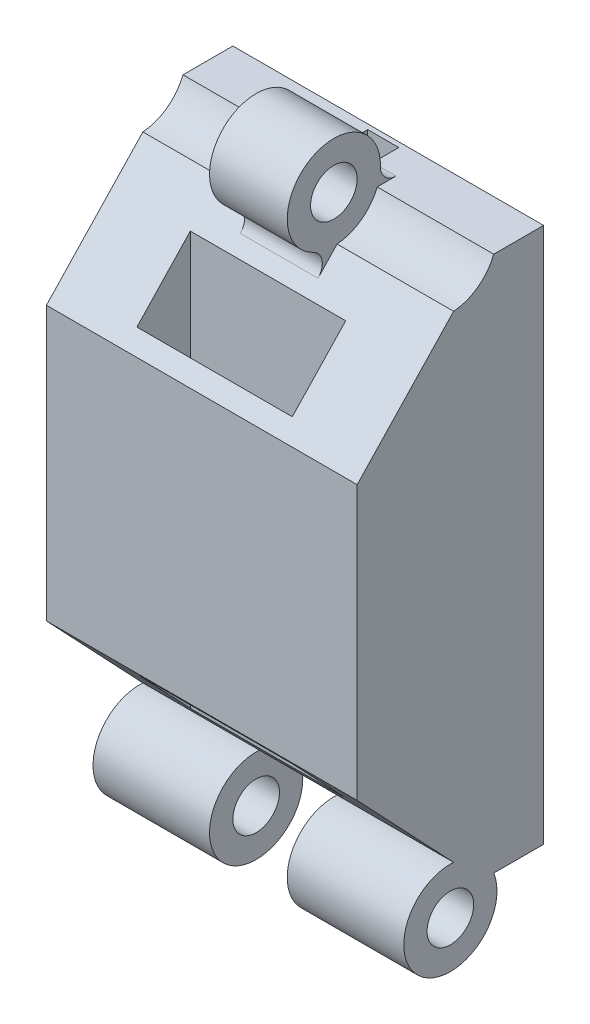
SolidWorks part; units mm, degrees
ref_plane "Front Plane" through (0, 0, 0) normal (0, 0, 1) x (1, 0, 0)
ref_plane "Top Plane" through (0, 0, 0) normal (0, 1, 0) x (1, 0, 0)
ref_plane "Right Plane" through (0, 0, 0) normal (1, 0, 0) x (0, 0, -1)
sketch "Sketch2" plane through (0, 0, 0) normal (0, 0, 1) x (1, 0, 0)
  line L1 (-8, 17.25) -> (12, 17.25)
  line L2 (-8, -17.25) -> (12, -17.25)
  line L3 (12, -17.25) -> (12, 17.25)
  line L4 (-8, 17.25) -> (-8, -17.25)
  point P4 (0, 0)
  point P8 (2, 17.25)
  point P11 (2, -17.25)
extrude "Boss-Extrude1" add sketch "Sketch2" along normal blind 15
sketch "Sketch3" plane through (0, 17.25, 0) normal (0, 1, 0) x (1, 0, 0)
  line L1 (2, 0) -> (2, -15)
  line L2 (12, -15) -> (-8, -15) construction
ref_plane "Plane1" through (2, 0, 0) normal (1, 0, 0) x (0, 0, -1)
sketch "Sketch6" plane through (2, 0, 0) normal (1, 0, 0) x (0, 0, -1)
  line L0 (0, 17.25) -> (-4, 17.25)
  line L1 (0, 17.25) -> (-15, 17.25) construction
  line L2 (-4, 17.25) -> (-15, 5.631)
  line L3 (-15, -17.25) -> (-15, 17.25) construction
  line L4 (-15, 5.631) -> (-15, 17.25)
  line L5 (-15, 17.25) -> (-4, 17.25)
extrude "Cut-Extrude1" cut sketch "Sketch6" against normal through all both and the other way through all contours L2 L4 L5
sketch "Sketch8" plane through (2, 0, 0) normal (1, 0, 0) x (0, 0, -1)
  line L0 (0, -17.25) -> (-4, -17.25)
  line L1 (-15, -17.25) -> (0, -17.25) construction
  line L2 (-4, -17.25) -> (-15, -5.631)
  line L3 (-15, -17.25) -> (-15, 5.631) construction
  line L4 (-15, -5.631) -> (-15, -17.25)
  line L5 (-15, -17.25) -> (-4, -17.25)
extrude "Cut-Extrude2" cut sketch "Sketch8" against normal through all both and the other way through all contours L2 L4 L5
sketch "Sketch10" plane through (2, 0, 0) normal (1, 0, 0) x (0, 0, -1)
  line L0 (0, 17.25) -> (-6, 17.25)
  line L1 (-6, 17.25) -> (-6, 18.35)
  circle A0 centre (-6, 18.35) radius 1.5
  circle A1 centre (-6, 18.35) radius 3
extrude "Cut-Extrude4" cut sketch "Sketch10" against normal through all both and the other way through all contours A1
sketch "Sketch12" plane through (2, 0, 0) normal (1, 0, 0) x (0, 0, -1)
  circle A0 centre (-6, 18.35) radius 1.5
  circle A1 centre (-6, 18.35) radius 3
extrude "Boss-Extrude4" add sketch "Sketch12" along normal mid plane 5
fillet "Fillet4" radius 1 2 edges at (2, 17.25, 3.2089) (2, 15.3572, 5.7919)
sketch "Sketch13" plane through (2, 0, 0) normal (1, 0, 0) x (0, 0, -1)
  line L0 (-6, -17.25) -> (-6, -18.35)
  line L1 (0, -17.25) -> (-6, -17.25)
  circle A0 centre (-6, -18.35) radius 1.5
  circle A1 centre (-6, -18.35) radius 3
extrude "Boss-Extrude5" add sketch "Sketch13" along normal up to surface and the other way up to surface contours A1 | A0 up to face at (12, 2.1405, 6.1039) other way up to face at (-8, 2.1405, 6.1039)
sketch "Sketch14" plane through (2, 0, 0) normal (1, 0, 0) x (0, 0, -1)
  circle A1 centre (-6, -18.35) radius 3
extrude "Cut-Extrude6" cut sketch "Sketch14" against normal mid plane 5 contours A1
sketch "Sketch15" plane through (2, 0, 0) normal (1, 0, 0) x (0, 0, -1)
  line L0 (0, 0) -> (-12, 0)
  line L2 (0, -17.25) -> (0, 17.25) construction
  line L3 (-12, 0) -> (-12, 8.7999)
  line L4 (-5.7919, 15.3572) -> (-15, 5.631) construction
  line L5 (-12, 8.7999) -> (-16.5481, 8.7999)
  line L6 (-16.5481, 8.7999) -> (-16.5481, -7.0423)
  line L7 (-16.5481, -7.0423) -> (-16.5481, -12.2335)
  line L8 (-16.5481, -12.2335) -> (-12, -12.2335)
  line L9 (-12, -12.2335) -> (-12, 0)
extrude "Cut-Extrude7" cut sketch "Sketch15" against normal through all both and the other way through all contours L8 L9 L3 L5 L6 L7
sketch "Sketch16" plane through (0, 10.1503, 10.7215) normal (0, 0.6875, 0.7262) x (1, 0, 0)
  line L0 (2, -1.8597) -> (2, -0.6597)
  line L1 (-8, -1.8597) -> (12, -1.8597) construction
  line L2 (2, -0.6597) -> (7, -0.6597)
  line L3 (7, -0.6597) -> (7, 4.3403)
  line L4 (7, 4.3403) -> (-3, 4.3403)
  line L5 (-3, 4.3403) -> (-3, -0.6597)
  line L6 (-3, -0.6597) -> (2, -0.6597)
sketch "Sketch17" plane through (0, 0, 0) normal (0, 1, 0) x (1, 0, 0)
  line L0 (-3, -7.7375) -> (-3, -11.175)
  line L1 (-3, -11.175) -> (7, -11.175)
  line L2 (7, -11.175) -> (7, -7.7375)
  line L3 (7, -7.7375) -> (-3, -7.7375)
extrude "Cut-Extrude8" cut sketch "Sketch17" against normal up to surface and the other way up to surface up to face at (2, -13.1714, 7.8613) other way up to face at (2, 13.3942, 7.6504)
sketch "Sketch18" plane through (2, 0, 0) normal (1, 0, 0) x (0, 0, -1)
  line L0 (-0.32, -17.25) -> (-2.32, -17.25)
  line L1 (-3.2089, -17.25) -> (0, -17.25) construction
  line L2 (-2.32, -17.25) -> (-2.32, 21.5987)
  line L3 (-2.32, 21.5987) -> (-0.32, 21.5987)
  line L4 (-0.32, 21.5987) -> (-0.32, -17.25)
extrude "Cut-Extrude9" cut sketch "Sketch18" against normal mid plane 2
